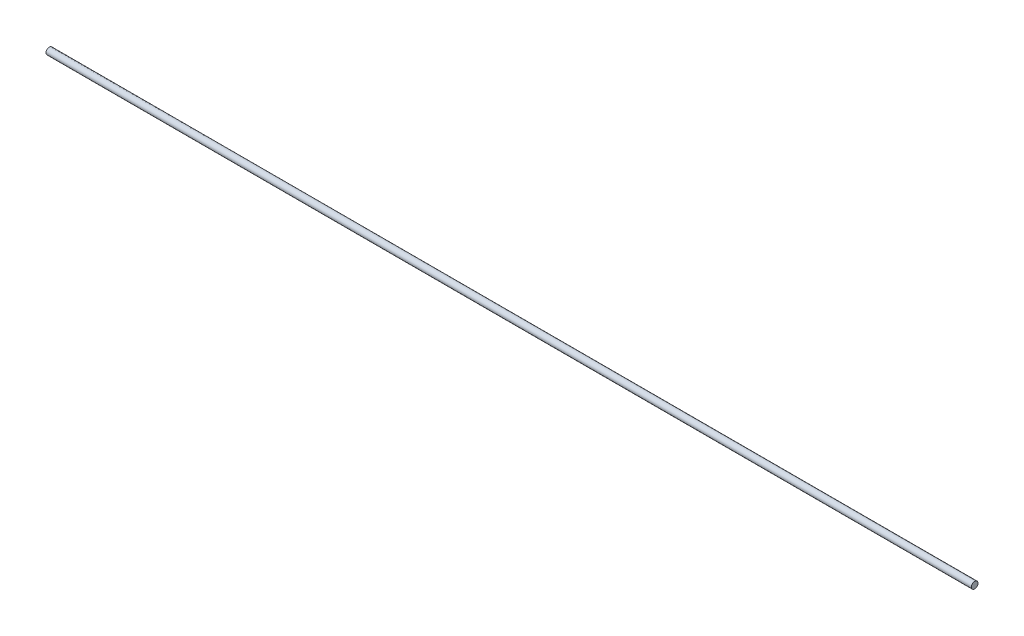
SolidWorks part; units mm, degrees
ref_plane "Front Plane" through (0, 0, 0) normal (0, 0, 1) x (1, 0, 0)
ref_plane "Top Plane" through (0, 0, 0) normal (0, 1, 0) x (1, 0, 0)
ref_plane "Right Plane" through (0, 0, 0) normal (1, 0, 0) x (0, 0, -1)
sketch "Sketch1" plane through (0, 0, 0) normal (0, 0, 1) x (1, 0, 0)
  line L1 (0, 0.5) -> (140, 0.5)
  line L2 (0, 0.5) -> (0, 0)
  line L3 (0, 0) -> (140, 0)
  line L4 (140, 0.5) -> (140, 0)
  dimension "D1" = 140
  dimension "D2" = 0.5
revolve "Revolve1" add sketch "Sketch1" angle 360 about L3
